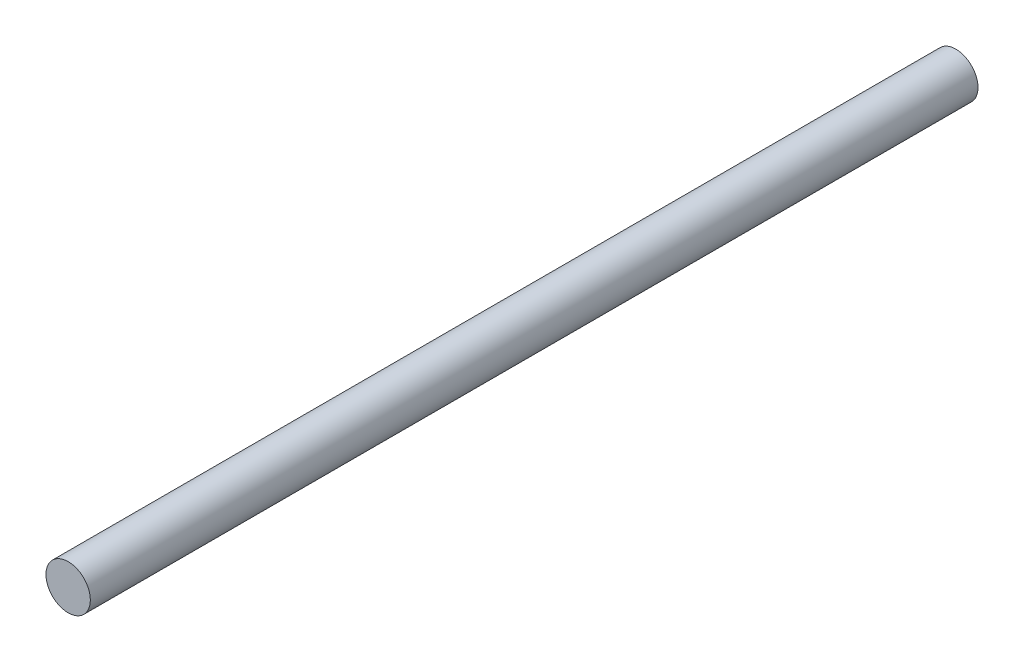
SolidWorks part; units mm, degrees
ref_plane "Front Plane" through (0, 0, 0) normal (0, 0, 1) x (1, 0, 0)
ref_plane "Top Plane" through (0, 0, 0) normal (0, 1, 0) x (1, 0, 0)
ref_plane "Right Plane" through (0, 0, 0) normal (1, 0, 0) x (0, 0, -1)
sketch "Sketch1" plane through (0, 0, 0) normal (0, 0, 1) x (1, 0, 0)
  circle A0 centre (0, 0) radius 2.5
  dimension "D1" = 5
extrude "Boss-Extrude1" add sketch "Sketch1" along normal blind 100
sketch "Sketch2" plane through (0, 0, 0) normal (0, 0, -1) x (-1, 0, 0)
  line L0 (0, 2.5) -> (0, 0)
  line L1 (0, 0) -> (0, -2.5)
  circle A0 centre (0, 0) radius 2.5 construction
